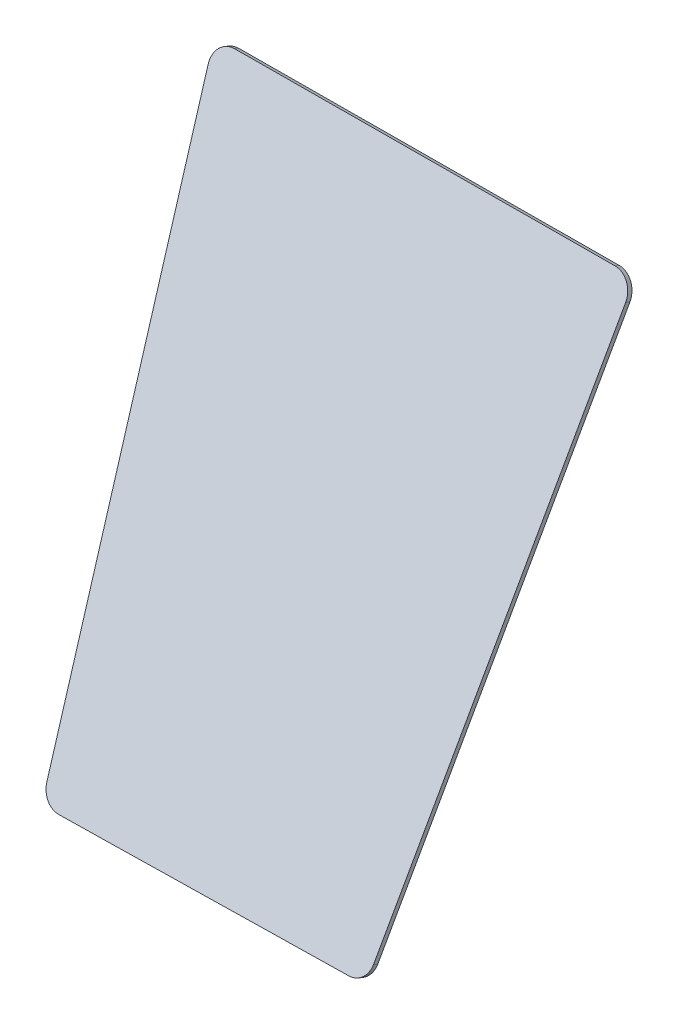
SolidWorks part; units mm, degrees
material "Acrylic (Medium-high impact)"
ref_plane "Front Plane" through (0, 0, 0) normal (0, 0, 1) x (1, 0, 0)
ref_plane "Top Plane" through (0, 0, 0) normal (0, 1, 0) x (1, 0, 0)
ref_plane "Right Plane" through (0, 0, 0) normal (1, 0, 0) x (0, 0, -1)
sketch "Sketch1" plane through (0, 407.8865, 975.0283) normal (0, 0.3859, 0.9225) x (1, 0, 0)
  line L0 (144.3312, 73.3437) -> (-144.3312, 72.0634) construction
  line L1 (110.6784, -319.2528) -> (144.3312, 73.3437) construction
  line L2 (-110.6784, -322.3786) -> (110.6784, -319.2528) construction
  line L3 (-144.3312, 72.0634) -> (-110.6784, -322.3786) construction
  line L4 (144.3312, 73.3437) -> (-144.3312, 72.0634)
  line L5 (110.6784, -319.2528) -> (144.3312, 73.3437)
  line L6 (-110.6784, -322.3786) -> (110.6784, -319.2528)
  line L7 (-144.3312, 72.0634) -> (-110.6784, -322.3786)
extrude "Boss-Extrude1" add sketch "Sketch1" against normal up to vertex (3.175 mm away) from vertex at 0
fillet "Fillet1" radius 12.7 4 edges at (-144.3312, 473.7545, 945.7528) (-110.6784, 109.8698, 1097.9777) (110.6784, 112.7535, 1096.7714) (144.3312, 474.9356, 945.2587)
